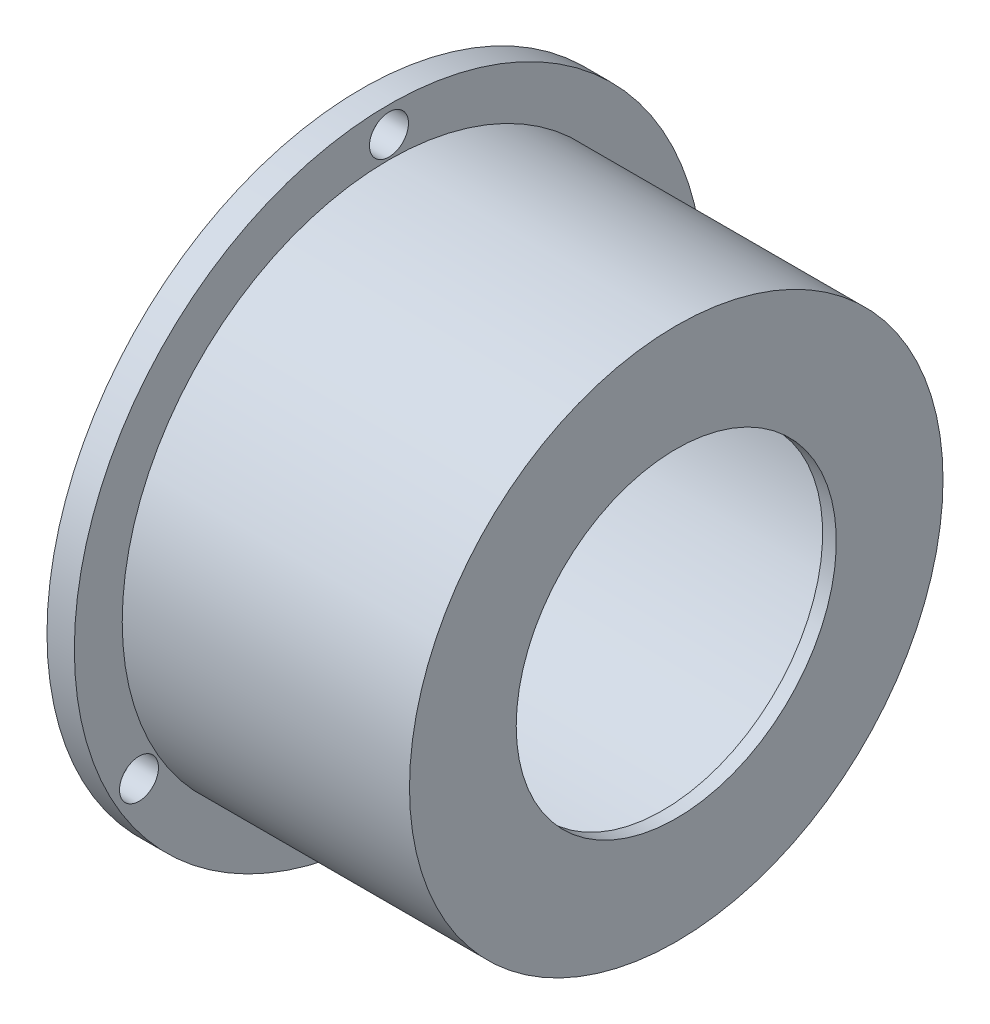
SolidWorks part; units mm, degrees
ref_plane "Front Plane" through (0, 0, 0) normal (0, 0, 1) x (1, 0, 0)
ref_plane "Top Plane" through (0, 0, 0) normal (0, 1, 0) x (1, 0, 0)
ref_plane "Right Plane" through (0, 0, 0) normal (1, 0, 0) x (0, 0, -1)
sketch "Axial profile (mm)" plane through (0, 0, 0) normal (0, 0, 1) x (1, 0, 0)
  line L0 (-110, 0) -> (75, 0) construction
  line L1 (135.7, 36.4) -> (179.7, 36.4)
  line L2 (179.7, 36.4) -> (179.7, 23.4)
  line L3 (179.7, 23.4) -> (181.7, 23.4)
  line L4 (181.7, 23.4) -> (181.7, 39)
  line L5 (181.7, 39) -> (139.7, 39)
  line L6 (139.7, 39) -> (139.7, 46)
  line L7 (139.7, 46) -> (135.7, 46)
  line L8 (135.7, 46) -> (135.7, 36.4)
revolve "Full revolution" add sketch "Axial profile (mm)" angle 360 about L0
sketch "Sketch2" plane through (0, 0, 0) normal (1, 0, 0) x (0, 0, -1)
  circle A0 centre (0, 42.2) radius 1.65
  circle A1 centre (-36.5463, -21.1) radius 1.65
  circle A2 centre (36.5463, -21.1) radius 1.65
extrude "Axial holes" cut sketch "Sketch2" along normal through all and the other way through all
sketch "Sketch3" plane through (0, 0, 0) normal (1, 0, 0) x (0, 0, -1)
  circle A0 centre (0, 42.2) radius 2.85
  circle A1 centre (-36.5463, -21.1) radius 2.85
  circle A2 centre (36.5463, -21.1) radius 2.85
extrude "Cut-Extrude2" cut sketch "Sketch3" along normal blind 4 from offset 135.7
